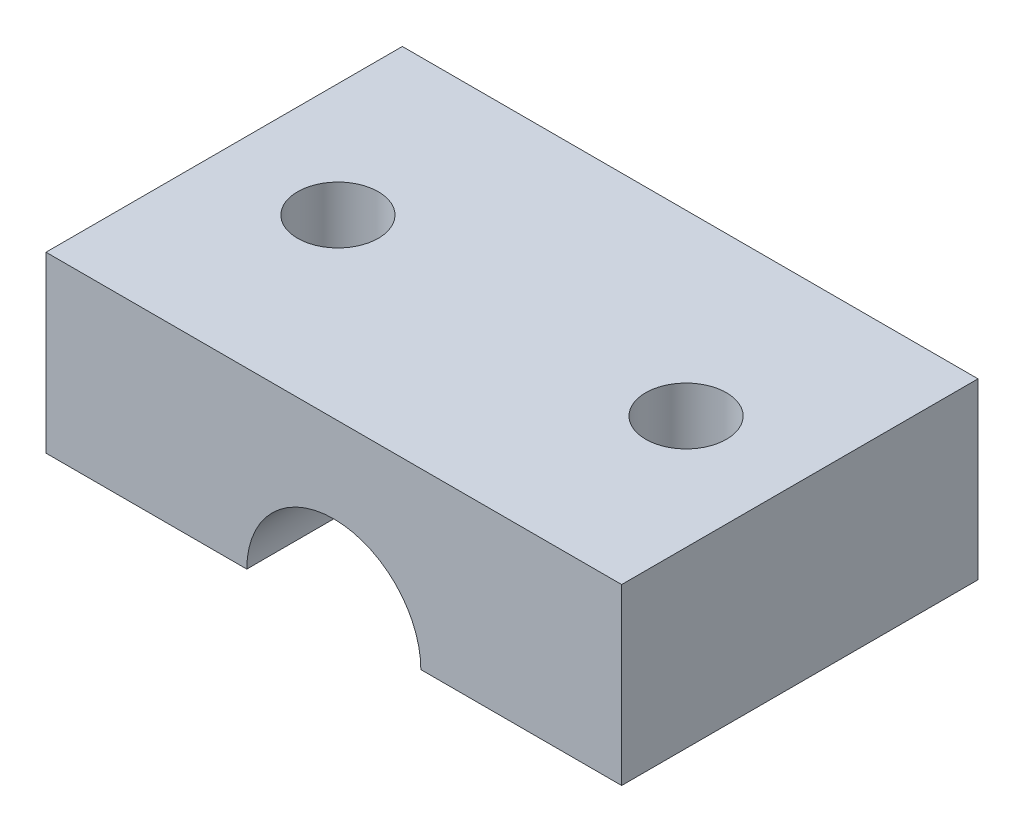
SolidWorks part; units mm, degrees
ref_plane "Front Plane" through (0, 0, 0) normal (0, 0, 1) x (1, 0, 0)
ref_plane "Top Plane" through (0, 0, 0) normal (0, 1, 0) x (1, 0, 0)
ref_plane "Right Plane" through (0, 0, 0) normal (1, 0, 0) x (0, 0, -1)
sketch "Sketch1" plane through (0, 0, 0) normal (0, 1, 0) x (1, 0, 0)
  line L0 (31, 0) -> (31, -13)
  line L1 (0, 0) -> (41, 0)
  line L2 (0, 0) -> (0, -13)
  line L3 (0, -13) -> (41, -13)
  line L4 (41, 0) -> (41, -13)
  line L5 (10, 0) -> (10, -13)
  circle A0 centre (14.15, -6.5) radius 1.4732
  circle A1 centre (26.85, -6.5) radius 1.4732
  point P5 (14.15, -6.5)
  point P6 (26.85, -6.5)
  dimension "D6" = 2.9464
  dimension "D1" = 41
  dimension "D2" = 13
  dimension "D3" = 6.5
  dimension "D4" = 14.15
  dimension "D5" = 12.7
  dimension "D7" = 10
  dimension "D8" = 10
extrude "Boss-Extrude1" add sketch "Sketch1" along normal blind 6.35 contours L1 L5 L3 L0 A1 A0
sketch "Sketch2" plane through (0, 0, 0) normal (0, 0, -1) x (-1, 0, 0)
  line L1 (-10, 0) -> (-31, 0) construction
  circle A0 centre (-20.5, 0) radius 3.175
  point P2 (-20.0481, 3.3883)
  point P4 (0, 0)
  point P5 (0, 0)
  dimension "D1" = 6.35
extrude "Cut-Extrude1" cut sketch "Sketch2" against normal up to surface (13 mm away) up to face at (20.5, 3.175, 13)
equation "\"D4@Sketch1\"=(41-12.7)/2"
equation "\"D8@Sketch1\"=\"D7@Sketch1\""
